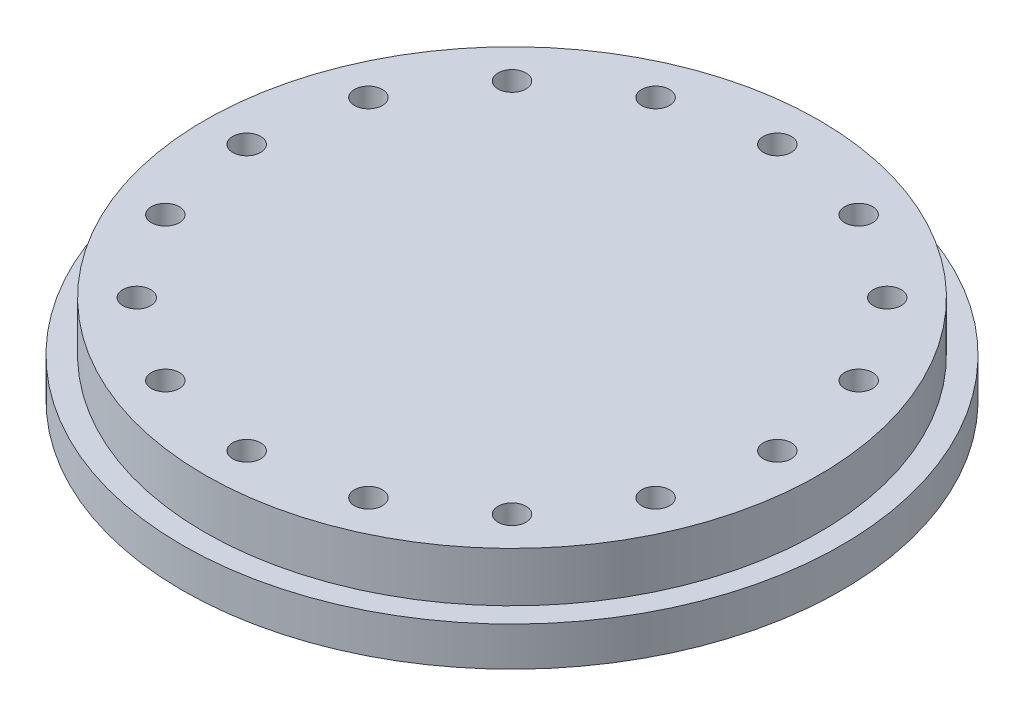
SolidWorks part; units mm, degrees
material "6061-T6 (SS)"
ref_plane "Front Plane" through (0, 0, 0) normal (0, 0, 1) x (1, 0, 0)
ref_plane "Top Plane" through (0, 0, 0) normal (0, 1, 0) x (1, 0, 0)
ref_plane "Right Plane" through (0, 0, 0) normal (1, 0, 0) x (0, 0, -1)
sketch "Sketch1" plane through (0, 0, 0) normal (0, 1, 0) x (1, 0, 0)
  circle A0 centre (0, 0) radius 29.5
  dimension "D1" = 59
extrude "Boss-Extrude1" add sketch "Sketch1" along normal mid plane 3.5
sketch "Sketch2" plane through (0, 1.75, 0) normal (0, 1, 0) x (1, 0, 0)
  circle A0 centre (0, 0) radius 27.5
  dimension "D1" = 55
extrude "Boss-Extrude2" add sketch "Sketch2" along normal blind 4.45
sketch "Sketch3" plane through (0, -1.75, 0) normal (0, -1, 0) x (1, 0, 0)
  circle A0 centre (0, 0) radius 23.75 construction
  circle A1 centre (0, 23.75) radius 1.25
  dimension "D1" = 47.5
  dimension "D2" = 2.5
extrude "Cut-Extrude1" cut sketch "Sketch3" against normal through all
pattern_circular "CirPattern1" count 16 over 360 about axis through (0, 0, 0) along (0, 1, 0) of "Cut-Extrude1"
